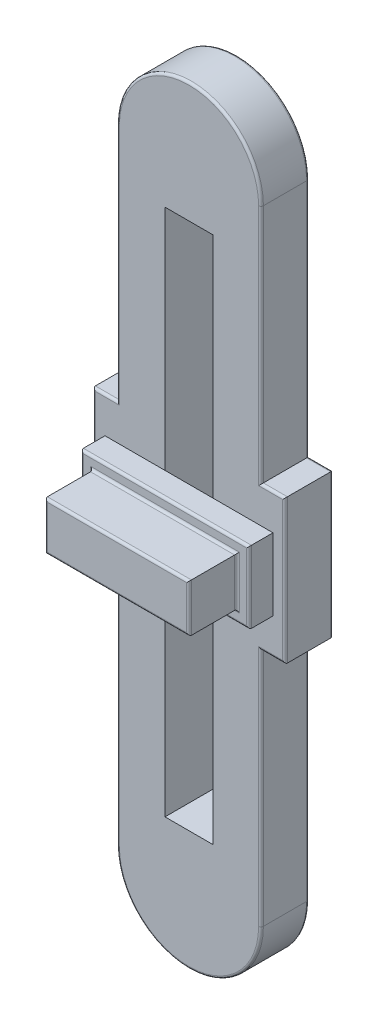
SolidWorks part; units mm, degrees
ref_plane "Front Plane" through (0, 0, 0) normal (0, 0, 1) x (1, 0, 0)
ref_plane "Top Plane" through (0, 0, 0) normal (0, 1, 0) x (1, 0, 0)
ref_plane "Right Plane" through (0, 0, 0) normal (1, 0, 0) x (0, 0, -1)
sketch "Sketch1" plane through (0, 0, 0) normal (0, 0, 1) x (1, 0, 0)
  line L0 (0, 0) -> (0, -260) construction
  line L1 (30, 0) -> (30, -100)
  line L2 (-30, 0) -> (-30, -100)
  line L3 (-30, -130) -> (30, -130) construction
  line L4 (-10, -240) -> (10, -240)
  line L5 (-10, -240) -> (-10, -20)
  line L6 (-10, -20) -> (10, -20)
  line L7 (10, -240) -> (10, -20)
  line L8 (-10, -240) -> (10, -20) construction
  line L9 (-10, -20) -> (10, -240) construction
  line L10 (-30, -160) -> (-30, -260)
  line L11 (-30, -100) -> (-40, -100)
  line L13 (-30, -160) -> (-40, -160)
  line L14 (-40, -100) -> (-40, -160)
  line L15 (30, -100) -> (40, -100)
  line L17 (30, -160) -> (40, -160)
  line L18 (40, -100) -> (40, -160)
  line L19 (30, -160) -> (30, -260)
  arc A0 (30, 0) -> (-30, 0) centre (0, 0) ccw
  arc A1 (-30, -260) -> (30, -260) centre (0, -260) ccw
  point P3 (0, -130)
  point P8 (0, -130)
  dimension "D2" = 30
  dimension "D1" = 260
  dimension "D3" = 220
  dimension "D4" = 20
  dimension "D5" = 10
  dimension "D6" = 60
  dimension "D7" = 20
extrude "Boss-Extrude1" add sketch "Sketch1" along normal blind 20
sketch "Sketch2" plane through (0, 0, 20) normal (0, 0, 1) x (1, 0, 0)
  line L0 (-40, -130) -> (40, -130) construction
  line L1 (-40, -100) -> (-40, -160) construction
  line L2 (40, -160) -> (40, -100) construction
  line L4 (-30, -120) -> (30, -120)
  line L5 (-30, -120) -> (-30, -140)
  line L6 (-30, -140) -> (30, -140)
  line L7 (30, -120) -> (30, -140)
  line L8 (-30, -120) -> (30, -140) construction
  line L9 (-30, -140) -> (30, -120) construction
  point P6 (0, -130)
  dimension "D1" = 60
  dimension "D2" = 20
extrude "Boss-Extrude2" add sketch "Sketch2" along normal blind 30
sketch "Sketch3" plane through (0, 0, 20) normal (0, 0, 1) x (1, 0, 0)
  line L0 (35, -115) -> (-35, -115)
  line L1 (-35, -115) -> (-35, -145)
  line L2 (-35, -145) -> (35, -145)
  line L3 (35, -145) -> (35, -115)
  line L4 (30, -140) -> (30, -120)
  line L5 (30, -120) -> (-30, -120)
  line L6 (-30, -120) -> (-30, -140)
  line L7 (-30, -140) -> (30, -140)
  line L8 (30, -140) -> (30, -120)
  line L9 (30, -120) -> (-30, -120)
  line L10 (-30, -120) -> (-30, -140)
  line L11 (-30, -140) -> (30, -140)
  dimension "D1" = 0
  dimension "D2" = 5
extrude "Boss-Extrude3" add sketch "Sketch3" along normal blind 10
fillet "Fillet1" radius 1 12 edges at (0, -140, 50) (-30, -130, 50) (0, -120, 50) (30, -130, 50) (0, -120, 30) (-30, -130, 30) (0, -140, 30) (30, -130, 30) (0, -145, 30) (-35, -130, 30) (0, -115, 30) (35, -130, 30)
fillet "Fillet2" radius 1 24 edges at (-30, -210, 0) (0, -290, 0) (30, -50, 0) (-30, -50, 0) (-30, -210, 20) (0, -290, 20) (30, -50, 20) (-30, -50, 20) (-35, -160, 0) (-40, -130, 0) (-35, -100, 0) (35, -160, 0) (35, -100, 0) (40, -130, 0) (30, -210, 0) (0, 30, 0) (-35, -160, 20) (-35, -100, 20) (-40, -130, 20) (35, -160, 20) (35, -100, 20) (40, -130, 20) (30, -210, 20) (0, 30, 20)
